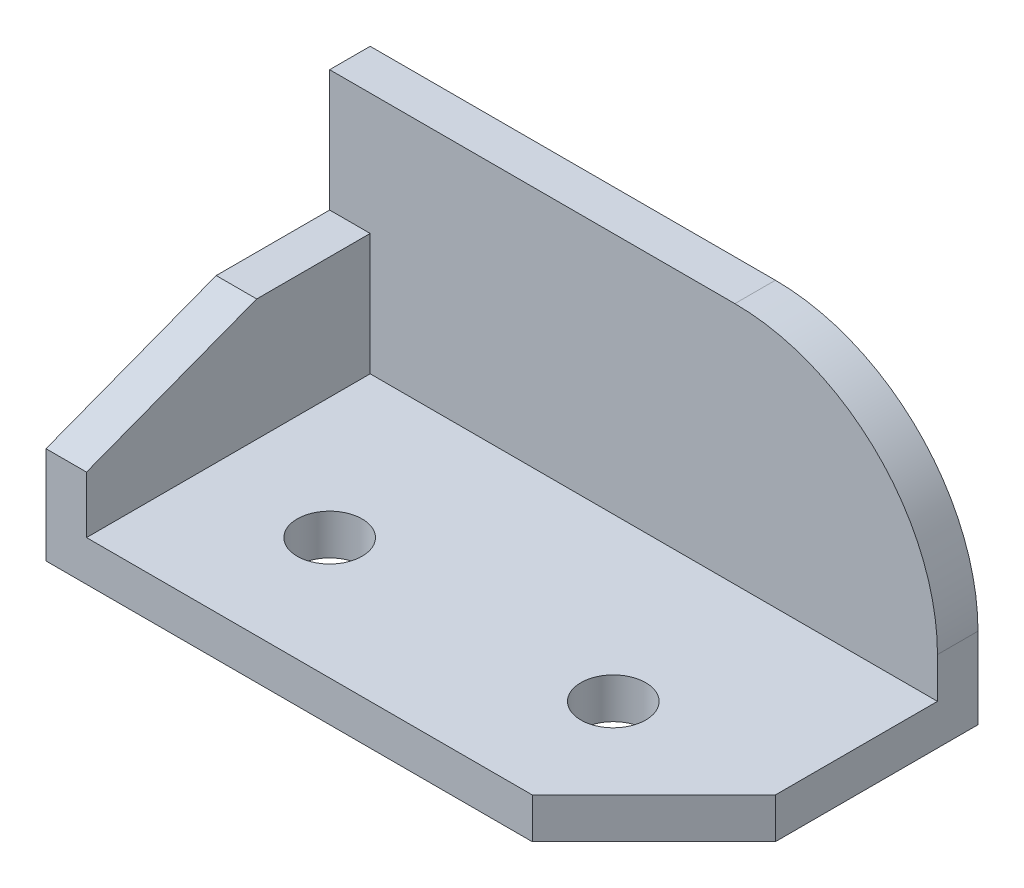
SolidWorks part; units mm, degrees
ref_plane "Front Plane" through (0, 0, 0) normal (0, 0, 1) x (1, 0, 0)
ref_plane "Top Plane" through (0, 0, 0) normal (0, 1, 0) x (1, 0, 0)
ref_plane "Right Plane" through (0, 0, 0) normal (1, 0, 0) x (0, 0, -1)
sketch "Sketch1" plane through (0, 0, 0) normal (0, 1, 0) x (1, 0, 0)
  line L0 (0, 0) -> (75, 0)
  line L1 (0, 0) -> (60, 0)
  line L2 (0, 0) -> (0, -40)
  line L3 (0, -40) -> (60, -40)
  line L5 (75, 0) -> (75, -25)
  line L6 (75, -25) -> (60, -40)
  line L8 (75, -25) -> (0, -25)
  line L9 (0, -25) -> (55, -25)
  line L10 (60, -40) -> (75, -25)
  circle A0 centre (55, -25) radius 4
  circle A1 centre (20, -25) radius 4
  dimension "D5" = 55
  dimension "D6" = 8
  dimension "D7" = 35
  dimension "D1" = 60
  dimension "D2" = 40
  dimension "D3" = 25
  dimension "D4" = 75
extrude "Boss-Extrude1" add sketch "Sketch1" along normal blind 5 contours A1 L9 A0 L8 L5 L0 L2 | A1 L9 L2 L3 L6 L8 A0
sketch "Sketch2" plane through (0, 0, 0) normal (-1, 0, 0) x (0, 0, 1)
  line L0 (40, 0) -> (40, 12)
  line L1 (40, 0) -> (0, 0)
  line L2 (0, 0) -> (0, 20)
  line L3 (0, 20) -> (19, 20)
  line L4 (19, 20) -> (40, 12)
  dimension "D1" = 19
extrude "Boss-Extrude2" add sketch "Sketch2" against normal blind 5
sketch "Sketch3" plane through (0, 0, 0) normal (0, 0, -1) x (-1, 0, 0)
  line L0 (0, 0) -> (0, 35)
  line L2 (0, 35) -> (-50, 35)
  line L4 (-75, 10) -> (-75, 0)
  line L5 (0, 0) -> (-74.5451, 0)
  line L6 (-75, 0) -> (-60, 0) construction
  line L11 (-75, 0) -> (-60, 0)
  line L12 (-75, 5) -> (-75, 0)
  line L13 (-60, 5) -> (-75, 5)
  line L14 (-60, 0) -> (-60, 5)
  line L15 (-74.5451, 0) -> (-60, 0)
  line L16 (-75, 5) -> (-75, 0)
  line L17 (-60, 5) -> (-75, 5)
  line L18 (-60, 0) -> (-60, 5)
  arc A0 (-50, 35) -> (-75, 10) centre (-50, 10) ccw
  line M4 (0, 20) -> (-5, 20)
  line M5 (-5, 20) -> (-5, 5)
  line M6 (-5, 5) -> (-75, 5)
  dimension "D1" = 25
  dimension "D3" = 35
  dimension "D2" = 0
extrude "Boss-Extrude3" add sketch "Sketch3" against normal blind 5 contours L2 A0 L4 L0 M6 M5 M4
